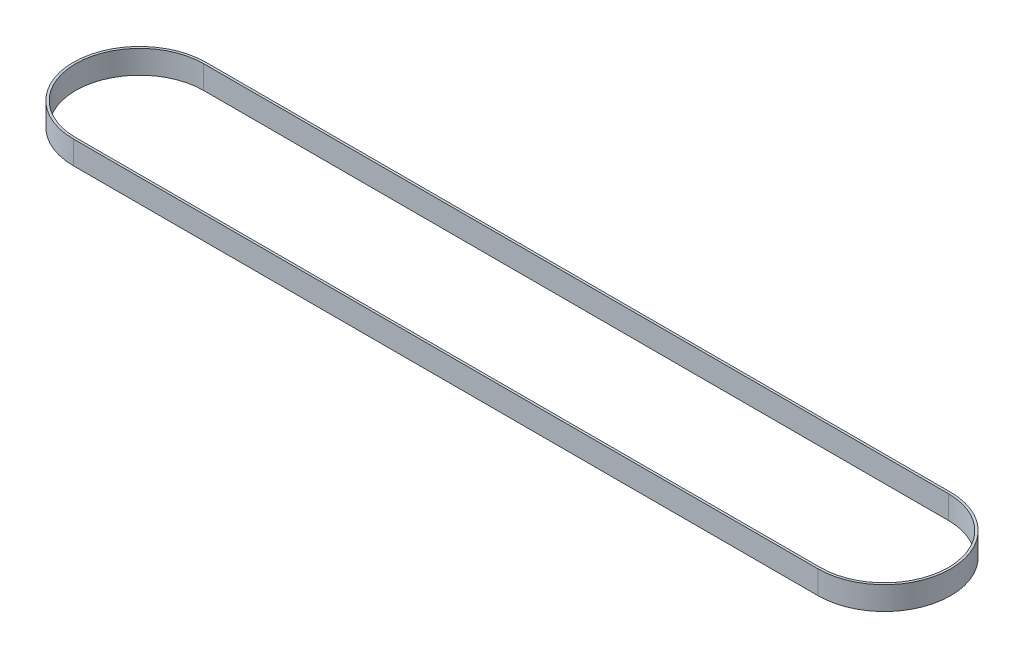
SolidWorks part; units mm, degrees
ref_plane "前视基准面" through (0, 0, 0) normal (0, 0, 1) x (1, 0, 0)
ref_plane "上视基准面" through (0, 0, 0) normal (0, 1, 0) x (1, 0, 0)
ref_plane "右视基准面" through (0, 0, 0) normal (1, 0, 0) x (0, 0, -1)
other "Configuration Table"
sketch "草图1" plane through (0, 0, 0) normal (0, 1, 0) x (1, 0, 0)
  line L0 (0, 0) -> (320, 0) construction
  line L1 (0, 27.5) -> (320, 27.5)
  line L2 (0, -27.5) -> (320, -27.5)
  line L3 (0, 0) -> (320, 0) construction
  line L4 (0, 28.5) -> (320, 28.5)
  line L5 (0, -28.5) -> (320, -28.5)
  arc A0 (0, 27.5) -> (0, -27.5) centre (0, 0) ccw
  arc A1 (320, -27.5) -> (320, 27.5) centre (320, 0) ccw
  arc A2 (0, 28.5) -> (0, -28.5) centre (0, 0) ccw
  arc A3 (320, -28.5) -> (320, 28.5) centre (320, 0) ccw
  point P3 (160, 0)
  point P8 (160, 0)
  dimension "D3" = 27.5
  dimension "D1" = 1
  dimension "D2" = 320
extrude "凸台-拉伸1" add sketch "草图1" along normal blind 10
